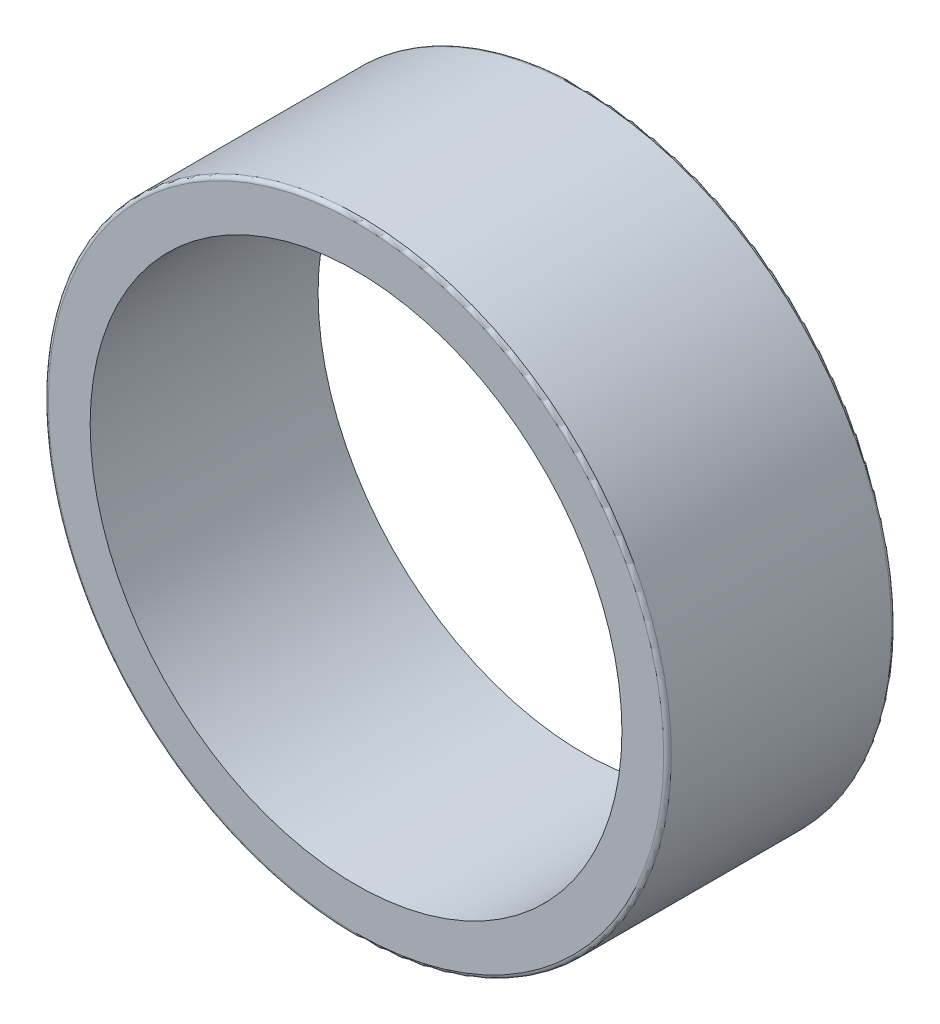
SolidWorks part; units mm, degrees
ref_plane "Front Plane" through (0, 0, 0) normal (0, 0, 1) x (1, 0, 0)
ref_plane "Top Plane" through (0, 0, 0) normal (0, 1, 0) x (1, 0, 0)
ref_plane "Right Plane" through (0, 0, 0) normal (1, 0, 0) x (0, 0, -1)
sketch "Sketch1" plane through (0, 0, 0) normal (0, 0, 1) x (1, 0, 0)
  circle A0 centre (0, 0) radius 3.5
  circle A1 centre (0, 0) radius 4.1
  dimension "D1" = 7
  dimension "D2" = 0.6
extrude "Boss-Extrude1" add sketch "Sketch1" along normal mid plane 3
fillet "Fillet1" radius 0.05 2 edges at (4.1, 0, -1.5) (4.1, 0, 1.5)
